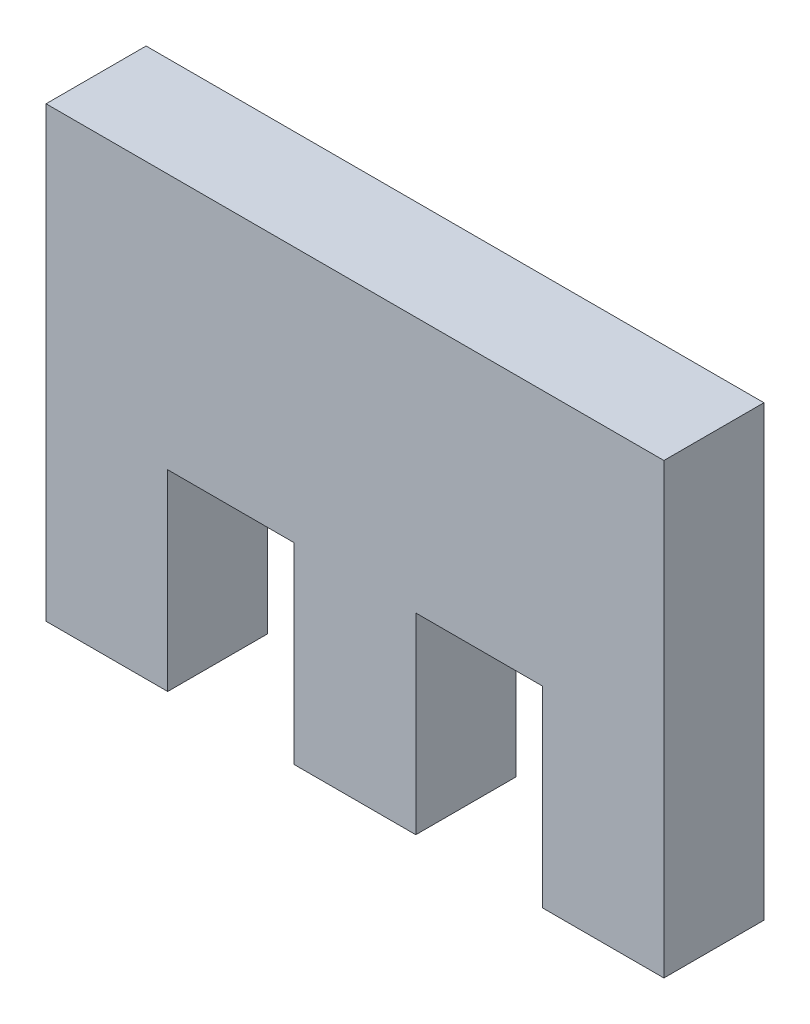
SolidWorks part; units mm, degrees
ref_plane "Front Plane" through (0, 0, 0) normal (0, 0, 1) x (1, 0, 0)
ref_plane "Top Plane" through (0, 0, 0) normal (0, 1, 0) x (1, 0, 0)
ref_plane "Right Plane" through (0, 0, 0) normal (1, 0, 0) x (0, 0, -1)
sketch "Sketch1" plane through (0, 0, 0) normal (0, 0, 1) x (1, 0, 0)
  line L0 (-20.0243, -3.0748) -> (-20.0243, 10.9252)
  line L1 (-20.0243, 10.9252) -> (-0.7243, 10.9252)
  line L2 (-0.7243, 10.9252) -> (-0.7243, -3.0748)
  line L3 (-0.7243, -3.0748) -> (-4.5243, -3.0748)
  line L4 (-4.5243, -3.0748) -> (-4.5243, 2.9252)
  line L5 (-4.5243, 2.9252) -> (-8.4743, 2.9252)
  line L6 (-8.4743, 2.9252) -> (-8.4743, -3.0748)
  line L7 (-8.4743, -3.0748) -> (-12.2743, -3.0748)
  line L8 (-12.2743, -3.0748) -> (-12.2743, 2.9252)
  line L9 (-12.2743, 2.9252) -> (-16.2243, 2.9252)
  line L10 (-16.2243, 2.9252) -> (-16.2243, -3.0748)
  line L11 (-16.2243, -3.0748) -> (-20.0243, -3.0748)
  dimension "D1" = 14
  dimension "D2" = 6
  dimension "D3" = 6
  dimension "D4" = 6
  dimension "D5" = 8
  dimension "D6" = 3.8
  dimension "D7" = 3.8
  dimension "D8" = 3.8
  dimension "D9" = 3.95
  dimension "D10" = 3.95
extrude "Boss-Extrude1" add sketch "Sketch1" along normal blind 3.125
